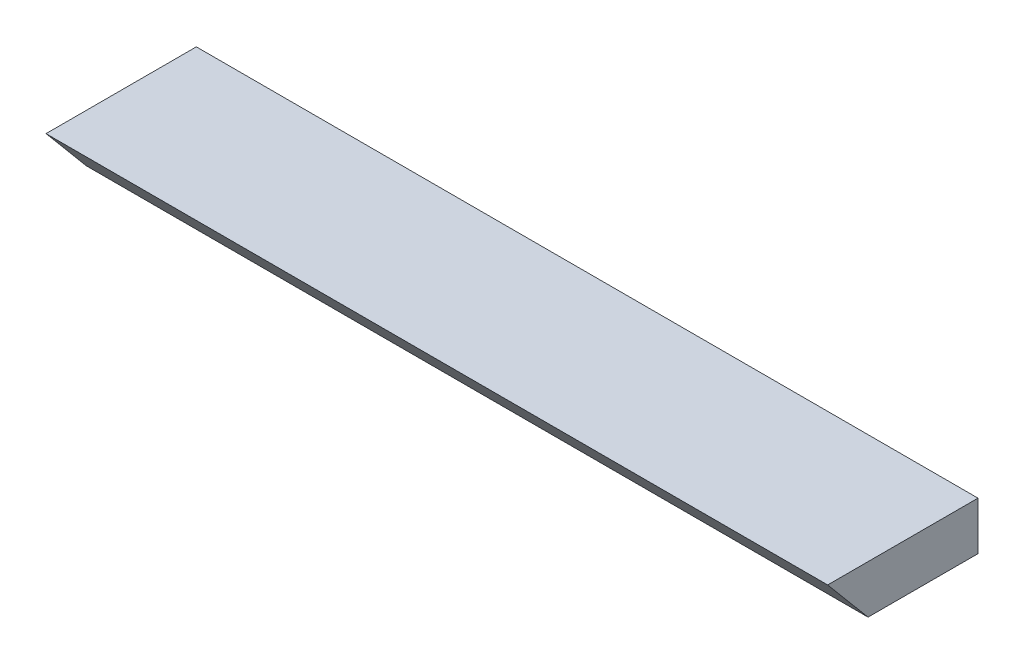
SolidWorks part; units mm, degrees
material "Листовая углеродистая сталь 1023 (SS)"
ref_plane "Спереди" through (0, 0, 0) normal (0, 0, 1) x (1, 0, 0)
ref_plane "Сверху" through (0, 0, 0) normal (0, 1, 0) x (1, 0, 0)
ref_plane "Справа" through (0, 0, 0) normal (1, 0, 0) x (0, 0, -1)
sketch "Эскиз1" plane through (0, 0, 0) normal (1, 0, 0) x (0, 0, -1)
  line L0 (-58.3707, 0.2459) -> (-65.0835, 8.2459)
  line L1 (-65.0835, 8.2459) -> (-40.0835, 8.2459)
  line L2 (-40.0835, 8.2459) -> (-40.0835, 0.2459)
  line L3 (-40.0835, 0.2459) -> (-58.3707, 0.2459)
  dimension "D1" = 50
  dimension "D2" = 8
  dimension "D3" = 25
extrude "Бобышка-Вытянуть1" add sketch "Эскиз1" along normal blind 130
